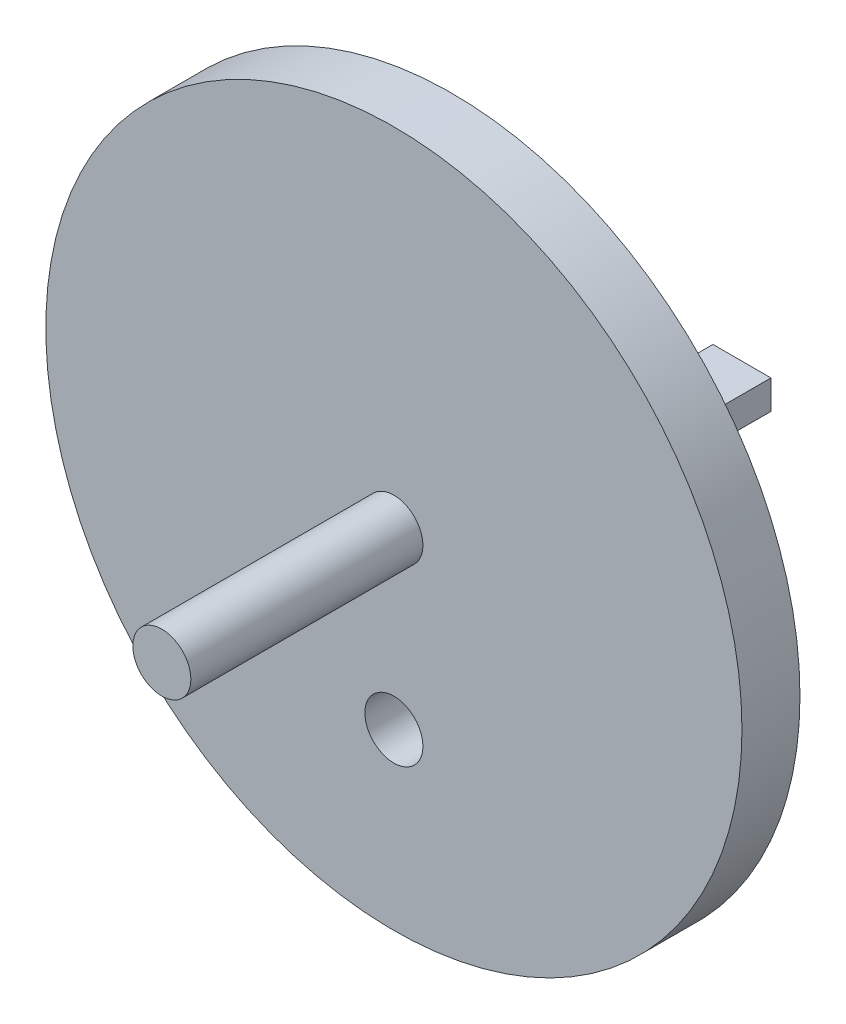
SolidWorks part; units mm, degrees
ref_plane "Front Plane" through (0, 0, 0) normal (0, 0, 1) x (1, 0, 0)
ref_plane "Top Plane" through (0, 0, 0) normal (0, 1, 0) x (1, 0, 0)
ref_plane "Right Plane" through (0, 0, 0) normal (1, 0, 0) x (0, 0, -1)
sketch "Sketch1" plane through (0, 0, 0) normal (0, 0, 1) x (1, 0, 0)
  circle A0 centre (0, 0) radius 60
  dimension "D1" = 120
extrude "Boss-Extrude1" add sketch "Sketch1" along normal blind 10
sketch "Sketch2" plane through (0, 0, 10) normal (0, 0, 1) x (1, 0, 0)
  circle A0 centre (0, 0) radius 5
  dimension "D1" = 10
extrude "Boss-Extrude2" add sketch "Sketch2" along normal blind 40
sketch "Sketch5" plane through (0, 0, 0) normal (0, 0, -1) x (-1, 0, 0)
  line L0 (0, 0) -> (0, -60) construction
  circle A0 centre (0, 0) radius 60 construction
  circle A1 centre (0, -30) radius 5
  dimension "D1" = 10
  dimension "D2" = 30
extrude "Cut-Extrude1" cut sketch "Sketch5" against normal blind 10
sketch "Sketch6" plane through (0, 0, 0) normal (0, 0, -1) x (-1, 0, 0)
  line L0 (0, -60) -> (0, 60) construction
  line L1 (0, 0) -> (-60, 0) construction
  line L2 (0, 0) -> (60, 0) construction
  line L3 (-51.9615, 30) -> (51.9615, 30) construction
  line L4 (45, 35) -> (45, 30)
  line L5 (-45, 35) -> (-35, 35)
  line L6 (-45, 35) -> (-45, 30)
  line L7 (-45, 30) -> (-35, 30)
  line L8 (-35, 35) -> (-35, 30)
  line L9 (35, 35) -> (35, 30)
  line L10 (45, 30) -> (35, 30)
  line L11 (45, 35) -> (35, 35)
  circle A0 centre (0, 0) radius 60 construction
  dimension "D1" = 30
  dimension "D2" = 5
  dimension "D3" = 10
  dimension "D4" = 35
extrude "Boss-Extrude4" add sketch "Sketch6" along normal blind 10
